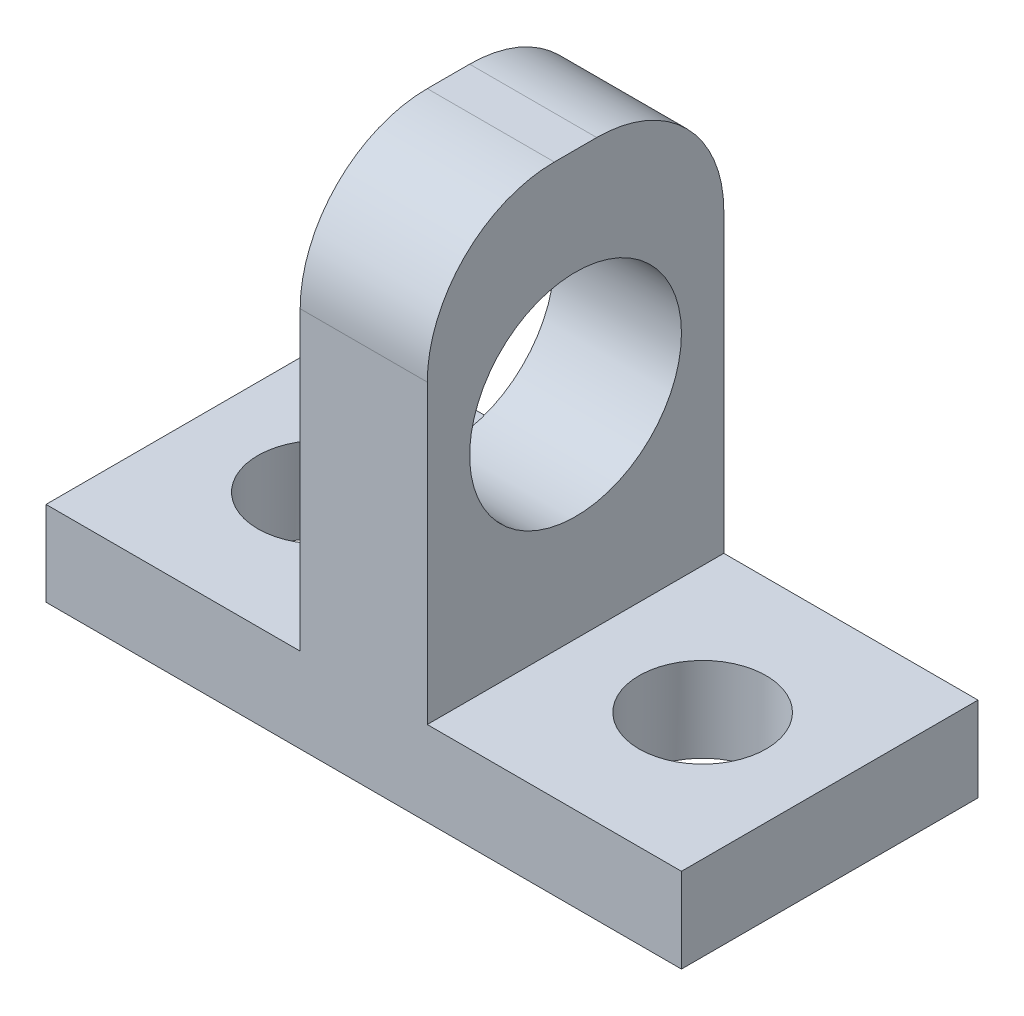
SolidWorks part; units mm, degrees
ref_plane "Front Plane" through (0, 0, 0) normal (0, 0, 1) x (1, 0, 0)
ref_plane "Top Plane" through (0, 0, 0) normal (0, 1, 0) x (1, 0, 0)
ref_plane "Right Plane" through (0, 0, 0) normal (1, 0, 0) x (0, 0, -1)
sketch "Sketch1" plane through (0, 0, 0) normal (0, 1, 0) x (1, 0, 0)
  line L1 (-7.5, -3.5) -> (7.5, -3.5)
  line L2 (-7.5, -3.5) -> (-7.5, 3.5)
  line L3 (-7.5, 3.5) -> (7.5, 3.5)
  line L4 (7.5, -3.5) -> (7.5, 3.5)
  line L5 (-7.5, -3.5) -> (7.5, 3.5) construction
  line L6 (-7.5, 3.5) -> (7.5, -3.5) construction
  point P0 (0, 0)
  dimension "D1" = 7
  dimension "D2" = 15
extrude "Boss-Extrude1" add sketch "Sketch1" along normal blind 2
sketch "Sketch2" plane through (0, 2, 0) normal (0, 1, 0) x (1, 0, 0)
  line L0 (7.5, 3.5) -> (-7.5, 3.5) construction
  line L1 (1.5, -3.5) -> (-1.5, -3.5)
  line L2 (1.5, -3.5) -> (1.5, 3.5)
  line L3 (1.5, 3.5) -> (-1.5, 3.5)
  line L4 (-1.5, -3.5) -> (-1.5, 3.5)
  line L5 (1.5, -3.5) -> (-1.5, 3.5) construction
  line L6 (1.5, 3.5) -> (-1.5, -3.5) construction
  point P0 (0, 0)
  dimension "D1" = 3
extrude "Boss-Extrude2" add sketch "Sketch2" along normal blind 10
sketch "Sketch3" plane through (1.5, 0, 0) normal (1, 0, 0) x (0, 0, -1)
  line L0 (3.5, 12) -> (3.5, 2) construction
  line L1 (-3.5, 12) -> (3.5, 12) construction
  circle A0 centre (0, 7) radius 2.5
  point P4 (3.5, 7)
  point P7 (0, 12)
  dimension "D1" = 5
extrude "Cut-Extrude1" cut sketch "Sketch3" against normal blind 10
fillet "Fillet1" radius 3 2 edges at (0, 12, -3.5) (0, 12, 3.5)
sketch "Sketch4" plane through (0, 2, 0) normal (0, 1, 0) x (1, 0, 0)
  line L0 (7.5, -3.5) -> (7.5, 3.5) construction
  circle A0 centre (4.5, 0) radius 1.5
  circle A1 centre (-4.5, 0) radius 1.5
  dimension "D1" = 3
  dimension "D2" = 9
  dimension "D3" = 3
extrude "Cut-Extrude2" cut sketch "Sketch4" against normal blind 10
